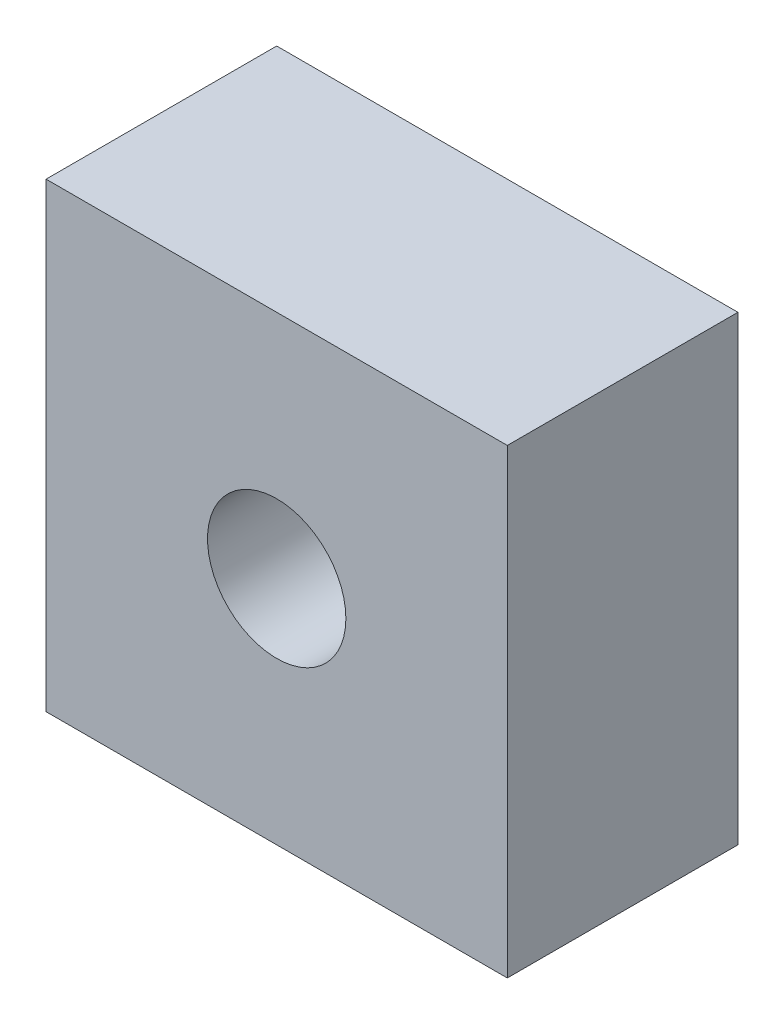
SolidWorks part; units mm, degrees
ref_plane "前视基准面" through (0, 0, 0) normal (0, 0, 1) x (1, 0, 0)
ref_plane "上视基准面" through (0, 0, 0) normal (0, 1, 0) x (1, 0, 0)
ref_plane "右视基准面" through (0, 0, 0) normal (1, 0, 0) x (0, 0, -1)
other "Configuration Table"
sketch "草图1" plane through (0, 0, 0) normal (0, 0, 1) x (1, 0, 0)
  line L1 (0, 0) -> (20, 0)
  line L2 (0, 0) -> (0, 20)
  line L3 (0, 20) -> (20, 20)
  line L4 (20, 0) -> (20, 20)
extrude "BaseBox" add sketch "草图1" along normal blind 10
sketch "草图2" plane through (0, 0, 10) normal (0, 0, 1) x (1, 0, 0)
  circle A0 centre (10, 10) radius 3
extrude "UpToSurfaceModify" cut sketch "草图2" against normal up to surface (10 mm away) up to face at (10, 10, 0)
